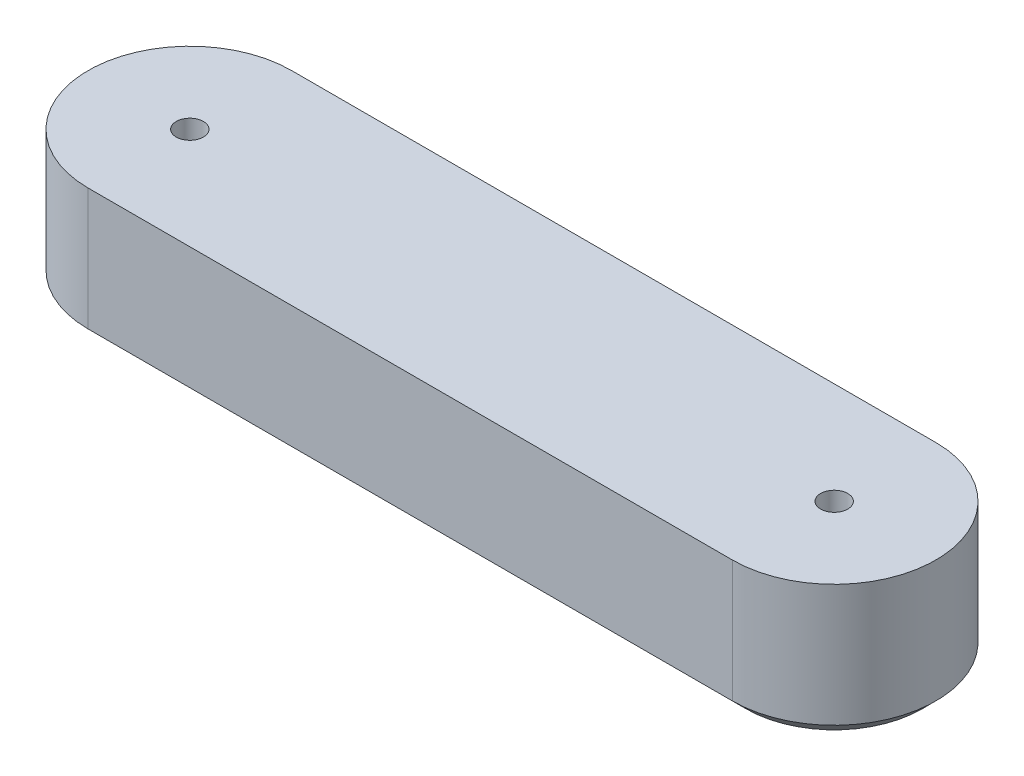
SolidWorks part; units mm, degrees
ref_plane "前视基准面" through (0, 0, 0) normal (0, 0, 1) x (1, 0, 0)
ref_plane "上视基准面" through (0, 0, 0) normal (0, 1, 0) x (1, 0, 0)
ref_plane "右视基准面" through (0, 0, 0) normal (1, 0, 0) x (0, 0, -1)
sketch "草图1" plane through (0, 0, 0) normal (0, 1, 0) x (1, 0, 0)
  line L1 (0, 0) -> (95, 0) construction
  line L2 (0, 15) -> (95, 15)
  line L3 (0, -15) -> (95, -15)
  arc A0 (0, 15) -> (0, -15) centre (0, 0) ccw
  arc A1 (95, -15) -> (95, 15) centre (95, 0) ccw
  point P5 (47.5, 0)
  dimension "D2" = 15
  dimension "D1" = 95
extrude "凸台-拉伸1" add sketch "草图1" along normal blind 20
sketch "草图3" plane through (0, 20, 0) normal (0, 1, 0) x (1, 0, 0)
  line L0 (0, 0) -> (95, 0) construction
  circle A0 centre (0, 0) radius 2
  circle A1 centre (95, 0) radius 2
  dimension "D1" = 4
  dimension "D3" = 95
  dimension "D2" = 2
extrude "切除-拉伸1" cut sketch "草图3" against normal blind 3
chamfer "倒角1" distance 2 angle 45 4 edges at (47.5, 0, 15) (110, 0, 0) (-15, 0, 0) (47.5, 0, -15)
